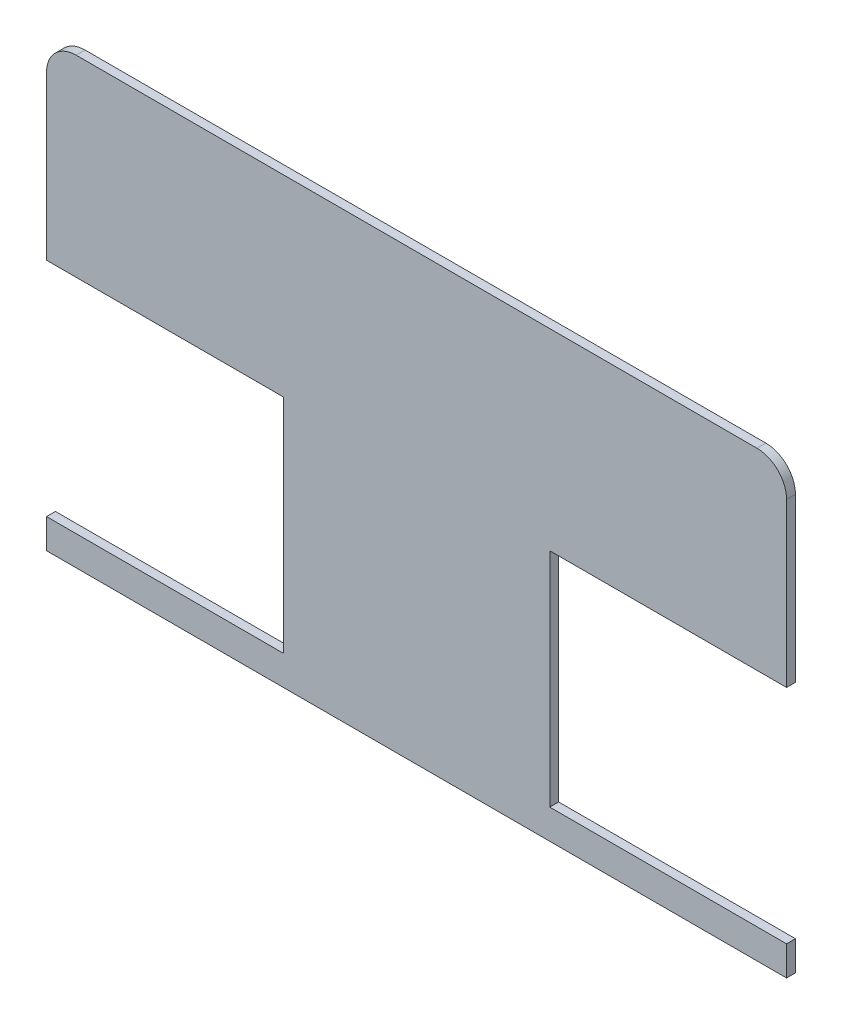
SolidWorks part; units mm, degrees
ref_plane "Front Plane" through (0, 0, 0) normal (0, 0, 1) x (1, 0, 0)
ref_plane "Top Plane" through (0, 0, 0) normal (0, 1, 0) x (1, 0, 0)
ref_plane "Right Plane" through (0, 0, 0) normal (1, 0, 0) x (0, 0, -1)
sketch "Sketch1" plane through (0, 0, 0) normal (0, 0, 1) x (1, 0, 0)
  line L0 (10, 0) -> (240, 0)
  line L1 (250, -10) -> (250, -65)
  line L2 (250, -65) -> (170, -65)
  line L3 (170, -65) -> (170, -140)
  line L4 (170, -140) -> (250, -140)
  line L5 (250, -140) -> (250, -150)
  line L6 (250, -150) -> (0, -150)
  line L7 (0, -150) -> (0, -140)
  line L8 (0, -140) -> (80, -140)
  line L9 (80, -140) -> (80, -65)
  line L10 (80, -65) -> (0, -65)
  line L11 (0, -65) -> (0, -10)
  arc A0 (240, 0) -> (250, -10) centre (240, -10) cw
  arc A1 (10, 0) -> (0, -10) centre (10, -10) ccw
  point P15 (250, 0)
  point P18 (0, 0)
  dimension "D9" = 10
  dimension "D1" = 250
  dimension "D2" = 150
  dimension "D3" = 75
  dimension "D4" = 80
  dimension "D5" = 10
  dimension "D6" = 75
  dimension "D7" = 80
  dimension "D8" = 10
extrude "Boss-Extrude1" add sketch "Sketch1" along normal blind 3
